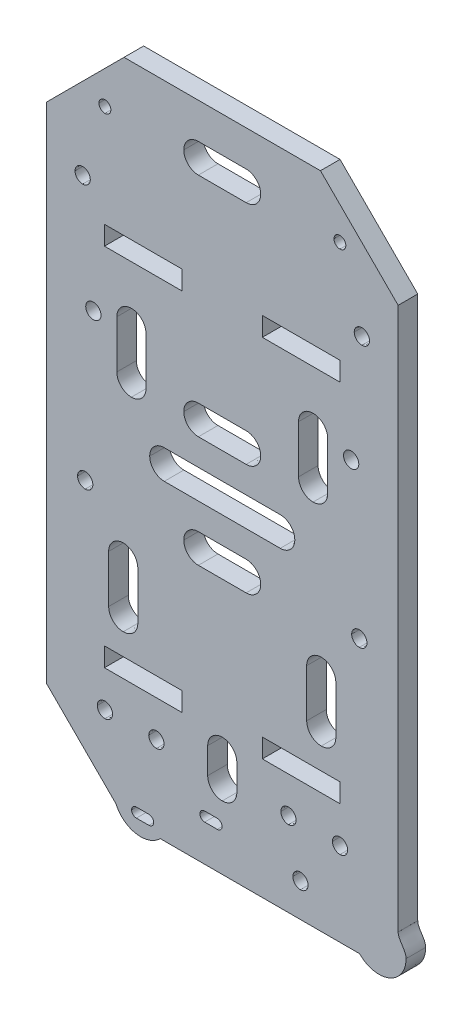
SolidWorks part; units mm, degrees
ref_plane "Front Plane" through (0, 0, 0) normal (0, 0, 1) x (1, 0, 0)
ref_plane "Top Plane" through (0, 0, 0) normal (0, 1, 0) x (1, 0, 0)
ref_plane "Right Plane" through (0, 0, 0) normal (1, 0, 0) x (0, 0, -1)
sketch "Model" plane through (0, 0, 0) normal (0, 0, 1) x (1, 0, 0)
  line L346 (206.5657, 107.1804) -> (231.766, 107.1804)
  line L347 (231.766, 107.1804) -> (231.766, 113.3307)
  line L348 (231.766, 113.3307) -> (206.5657, 113.3307)
  line L349 (206.5657, 113.3307) -> (206.5657, 107.1804)
  line L350 (257.7681, 107.1804) -> (282.967, 107.1804)
  line L351 (282.967, 107.1804) -> (282.967, 113.3307)
  line L352 (282.967, 113.3307) -> (257.7681, 113.3307)
  line L353 (257.7681, 113.3307) -> (257.7681, 107.1804)
  line L354 (212.9157, 163.4013) -> (187.7152, 138.2012)
  line L355 (187.7152, 138.2012) -> (187.7152, -24.9816)
  line L356 (187.7152, -24.9816) -> (210.2785, -47.5428)
  line L357 (224.6147, -50.1787) -> (289.3019, -50.1637)
  line L358 (301.8191, -37.8264) -> (301.8149, -37.8235)
  line L359 (301.8149, -37.8235) -> (301.8149, 138.2012)
  line L360 (301.8149, 138.2012) -> (276.6145, 163.4013)
  line L361 (276.6145, 163.4013) -> (212.9157, 163.4013)
  line L362 (206.5657, -11.2235) -> (231.766, -11.2235)
  line L363 (231.766, -11.2235) -> (231.766, -5.0731)
  line L364 (231.766, -5.0731) -> (206.5657, -5.0731)
  line L365 (206.5657, -5.0731) -> (206.5657, -11.2235)
  line L366 (257.7681, -11.2235) -> (282.967, -11.2235)
  line L367 (282.967, -11.2235) -> (282.967, -5.0731)
  line L368 (282.967, -5.0731) -> (257.7681, -5.0731)
  line L369 (257.7681, -5.0731) -> (257.7681, -11.2235)
  line L370 (220.0256, 89.3636) -> (220.0256, 73.8666)
  line L371 (210.5775, 73.8666) -> (210.5775, 89.3636)
  line L372 (278.9568, 89.3636) -> (278.9568, 73.8666)
  line L373 (269.5045, 73.8666) -> (269.5045, 89.3636)
  line L374 (239.063, -35.2158) -> (243.1413, -35.2158)
  line L375 (243.1413, -38.3181) -> (239.063, -38.3181)
  line L376 (237.0197, 42.2282) -> (252.5146, 42.2282)
  line L377 (252.5146, 32.7776) -> (237.0197, 32.7776)
  line L378 (225.9644, 60.2763) -> (263.574, 60.2763)
  line L379 (263.574, 50.827) -> (225.9644, 50.827)
  line L380 (237.0197, 78.3244) -> (252.5146, 78.3244)
  line L381 (252.5146, 68.8751) -> (237.0197, 68.8751)
  line L382 (216.9109, -45.1768) -> (220.9891, -45.1768)
  line L383 (220.9891, -48.2787) -> (216.9109, -48.2787)
  line L384 (217.3802, 22.1596) -> (217.3802, 6.6627)
  line L385 (207.9321, 6.6627) -> (207.9321, 22.1596)
  line L386 (281.6022, 22.1596) -> (281.6022, 6.6627)
  line L387 (272.15, 6.6627) -> (272.15, 22.1596)
  line L388 (249.4912, -16.3591) -> (249.4912, -24.7955)
  line L389 (240.0431, -24.7955) -> (240.0431, -16.3591)
  line L390 (237.0197, 151.8231) -> (252.5146, 151.8231)
  line L391 (252.5146, 142.3742) -> (237.0197, 142.3742)
  circle A0 centre (202.9651, 87.2011) radius 2.4743
  circle A1 centre (286.5734, 87.2011) radius 2.4743
  spline S738 degree 3 poles (210.2785, -47.5428) (211.6324, -50.6488) (214.7305, -52.8217) (218.3354, -52.8217) knots 0.2 0.2 0.2 0.2 0.266667 0.266667 0.266667 0.266667
  spline S739 degree 3 poles (218.3354, -52.8217) (220.7981, -52.8217) (223.0199, -51.8087) (224.6147, -50.1787) knots 0.266667 0.266667 0.266667 0.266667 0.333333 0.333333 0.333333 0.333333
  spline S740 degree 3 poles (289.3019, -50.1637) (290.8967, -51.8021) (293.1268, -52.8217) (295.5937, -52.8217) knots 0.4 0.4 0.4 0.4 0.466667 0.466667 0.466667 0.466667
  spline S741 degree 3 poles (295.5937, -52.8217) (298.0481, -52.8217) (300.2659, -51.8158) (301.8606, -50.1941) knots 0.466667 0.466667 0.466667 0.466667 0.533333 0.533333 0.533333 0.533333
  spline S742 degree 3 poles (301.8606, -50.1941) (303.4221, -48.608) (304.3856, -46.4318) (304.3856, -44.0314) knots 0.533333 0.533333 0.533333 0.533333 0.6 0.6 0.6 0.6
  spline S743 degree 3 poles (304.3856, -44.0314) (304.3856, -41.6085) (301.8315, -40.0711) (301.8191, -37.8264) knots 0.6 0.6 0.6 0.6 0.666667 0.666667 0.666667 0.666667
  spline S744 degree 3 poles (215.3037, 94.0893) (217.9201, 94.0893) (220.0256, 91.9808) (220.0256, 89.3636) knots 0 0 0 0 0.142857 0.142857 0.142857 0.142857
  spline S745 degree 3 poles (220.0256, 73.8666) (220.0256, 71.2498) (217.9201, 69.1426) (215.3037, 69.1426) knots 0.285714 0.285714 0.285714 0.285714 0.428571 0.428571 0.428571 0.428571
  spline S746 degree 3 poles (215.3037, 69.1426) (212.6873, 69.1426) (210.5775, 71.2498) (210.5775, 73.8666) knots 0.428571 0.428571 0.428571 0.428571 0.571429 0.571429 0.571429 0.571429
  spline S747 degree 3 poles (210.5775, 89.3636) (210.5775, 91.9808) (212.6873, 94.0893) (215.3037, 94.0893) knots 0.714286 0.714286 0.714286 0.714286 1 1 1 1
  spline S748 degree 3 poles (274.2307, 94.0893) (276.8471, 94.0893) (278.9568, 91.9808) (278.9568, 89.3636) knots 0 0 0 0 0.142857 0.142857 0.142857 0.142857
  spline S749 degree 3 poles (278.9568, 73.8666) (278.9568, 71.2498) (276.8471, 69.1426) (274.2307, 69.1426) knots 0.285714 0.285714 0.285714 0.285714 0.428571 0.428571 0.428571 0.428571
  spline S750 degree 3 poles (274.2307, 69.1426) (271.6143, 69.1426) (269.5045, 71.2498) (269.5045, 73.8666) knots 0.428571 0.428571 0.428571 0.428571 0.571429 0.571429 0.571429 0.571429
  spline S751 degree 3 poles (269.5045, 89.3636) (269.5045, 91.9808) (271.6143, 94.0893) (274.2307, 94.0893) knots 0.714286 0.714286 0.714286 0.714286 1 1 1 1
  spline S752 degree 3 poles (208.6381, 146.4724) (208.6381, 145.4088) (207.7784, 144.547) (206.7111, 144.547) knots 0 0 0 0 0.2 0.2 0.2 0.2
  spline S753 degree 3 poles (206.7111, 144.547) (205.6521, 144.547) (204.7882, 145.4088) (204.7882, 146.4724) knots 0.2 0.2 0.2 0.2 0.4 0.4 0.4 0.4
  spline S754 degree 3 poles (204.7882, 146.4724) (204.7882, 147.5347) (205.6521, 148.3973) (206.7111, 148.3973) knots 0.4 0.4 0.4 0.4 0.6 0.6 0.6 0.6
  spline S755 degree 3 poles (206.7111, 148.3973) (207.7784, 148.3973) (208.6381, 147.5347) (208.6381, 146.4724) knots 0.6 0.6 0.6 0.6 1 1 1 1
  spline S756 degree 3 poles (284.8374, 146.4724) (284.8374, 145.4088) (283.9778, 144.547) (282.9146, 144.547) knots 0 0 0 0 0.2 0.2 0.2 0.2
  spline S757 degree 3 poles (282.9146, 144.547) (281.8514, 144.547) (280.9876, 145.4088) (280.9876, 146.4724) knots 0.2 0.2 0.2 0.2 0.4 0.4 0.4 0.4
  spline S758 degree 3 poles (280.9876, 146.4724) (280.9876, 147.5347) (281.8514, 148.3973) (282.9146, 148.3973) knots 0.4 0.4 0.4 0.4 0.6 0.6 0.6 0.6
  spline S759 degree 3 poles (282.9146, 148.3973) (283.9778, 148.3973) (284.8374, 147.5347) (284.8374, 146.4724) knots 0.6 0.6 0.6 0.6 1 1 1 1
  spline S760 degree 3 poles (243.1413, -35.2158) (244.0009, -35.2158) (244.6945, -35.9077) (244.6945, -36.7678) knots 0.142857 0.142857 0.142857 0.142857 0.285714 0.285714 0.285714 0.285714
  spline S761 degree 3 poles (244.6945, -36.7678) (244.6945, -37.6262) (244.0009, -38.3181) (243.1413, -38.3181) knots 0.285714 0.285714 0.285714 0.285714 0.428571 0.428571 0.428571 0.428571
  spline S762 degree 3 poles (239.063, -38.3181) (238.2033, -38.3181) (237.5139, -37.6262) (237.5139, -36.7678) knots 0.571429 0.571429 0.571429 0.571429 0.714286 0.714286 0.714286 0.714286
  spline S763 degree 3 poles (237.5139, -36.7678) (237.5139, -35.9077) (238.2033, -35.2158) (239.063, -35.2158) knots 0.714286 0.714286 0.714286 0.714286 1 1 1 1
  spline S764 degree 3 poles (232.2936, 37.5029) (232.2936, 40.1197) (234.4033, 42.2282) (237.0197, 42.2282) knots 0 0 0 0 0.142857 0.142857 0.142857 0.142857
  spline S765 degree 3 poles (252.5146, 42.2282) (255.131, 42.2282) (257.2407, 40.1197) (257.2407, 37.5029) knots 0.285714 0.285714 0.285714 0.285714 0.428571 0.428571 0.428571 0.428571
  spline S766 degree 3 poles (257.2407, 37.5029) (257.2407, 34.8861) (255.131, 32.7776) (252.5146, 32.7776) knots 0.428571 0.428571 0.428571 0.428571 0.571429 0.571429 0.571429 0.571429
  spline S767 degree 3 poles (237.0197, 32.7776) (234.4033, 32.7776) (232.2936, 34.8861) (232.2936, 37.5029) knots 0.714286 0.714286 0.714286 0.714286 1 1 1 1
  spline S768 degree 3 poles (221.2383, 55.551) (221.2383, 58.1695) (223.3439, 60.2763) (225.9644, 60.2763) knots 0 0 0 0 0.142857 0.142857 0.142857 0.142857
  spline S769 degree 3 poles (263.574, 60.2763) (266.1904, 60.2763) (268.296, 58.1695) (268.296, 55.551) knots 0.285714 0.285714 0.285714 0.285714 0.428571 0.428571 0.428571 0.428571
  spline S770 degree 3 poles (268.296, 55.551) (268.296, 52.9342) (266.1904, 50.827) (263.574, 50.827) knots 0.428571 0.428571 0.428571 0.428571 0.571429 0.571429 0.571429 0.571429
  spline S771 degree 3 poles (225.9644, 50.827) (223.3439, 50.827) (221.2383, 52.9342) (221.2383, 55.551) knots 0.714286 0.714286 0.714286 0.714286 1 1 1 1
  spline S772 degree 3 poles (232.2936, 73.5992) (232.2936, 76.2172) (234.4033, 78.3244) (237.0197, 78.3244) knots 0 0 0 0 0.142857 0.142857 0.142857 0.142857
  spline S773 degree 3 poles (252.5146, 78.3244) (255.131, 78.3244) (257.2407, 76.2172) (257.2407, 73.5992) knots 0.285714 0.285714 0.285714 0.285714 0.428571 0.428571 0.428571 0.428571
  spline S774 degree 3 poles (257.2407, 73.5992) (257.2407, 70.9823) (255.131, 68.8751) (252.5146, 68.8751) knots 0.428571 0.428571 0.428571 0.428571 0.571429 0.571429 0.571429 0.571429
  spline S775 degree 3 poles (237.0197, 68.8751) (234.4033, 68.8751) (232.2936, 70.9823) (232.2936, 73.5992) knots 0.714286 0.714286 0.714286 0.714286 1 1 1 1
  spline S776 degree 3 poles (220.9891, -45.1768) (221.8488, -45.1768) (222.5423, -45.8683) (222.5423, -46.7267) knots 0.142857 0.142857 0.142857 0.142857 0.285714 0.285714 0.285714 0.285714
  spline S777 degree 3 poles (222.5423, -46.7267) (222.5423, -47.5868) (221.8488, -48.2787) (220.9891, -48.2787) knots 0.285714 0.285714 0.285714 0.285714 0.428571 0.428571 0.428571 0.428571
  spline S778 degree 3 poles (216.9109, -48.2787) (216.0512, -48.2787) (215.3618, -47.5868) (215.3618, -46.7267) knots 0.571429 0.571429 0.571429 0.571429 0.714286 0.714286 0.714286 0.714286
  spline S779 degree 3 poles (215.3618, -46.7267) (215.3618, -45.8683) (216.0512, -45.1768) (216.9109, -45.1768) knots 0.714286 0.714286 0.714286 0.714286 1 1 1 1
  spline S780 degree 3 poles (212.6582, 26.8849) (215.2746, 26.8849) (217.3802, 24.7764) (217.3802, 22.1596) knots 0 0 0 0 0.142857 0.142857 0.142857 0.142857
  spline S781 degree 3 poles (217.3802, 6.6627) (217.3802, 4.0454) (215.2746, 1.9386) (212.6582, 1.9386) knots 0.285714 0.285714 0.285714 0.285714 0.428571 0.428571 0.428571 0.428571
  spline S782 degree 3 poles (212.6582, 1.9386) (210.0418, 1.9386) (207.9321, 4.0454) (207.9321, 6.6627) knots 0.428571 0.428571 0.428571 0.428571 0.571429 0.571429 0.571429 0.571429
  spline S783 degree 3 poles (207.9321, 22.1596) (207.9321, 24.7764) (210.0418, 26.8849) (212.6582, 26.8849) knots 0.714286 0.714286 0.714286 0.714286 1 1 1 1
  spline S784 degree 3 poles (276.8761, 26.8849) (279.4925, 26.8849) (281.6022, 24.7764) (281.6022, 22.1596) knots 0 0 0 0 0.142857 0.142857 0.142857 0.142857
  spline S785 degree 3 poles (281.6022, 6.6627) (281.6022, 4.0454) (279.4925, 1.9386) (276.8761, 1.9386) knots 0.285714 0.285714 0.285714 0.285714 0.428571 0.428571 0.428571 0.428571
  spline S786 degree 3 poles (276.8761, 1.9386) (274.2597, 1.9386) (272.15, 4.0454) (272.15, 6.6627) knots 0.428571 0.428571 0.428571 0.428571 0.571429 0.571429 0.571429 0.571429
  spline S787 degree 3 poles (272.15, 22.1596) (272.15, 24.7764) (274.2597, 26.8849) (276.8761, 26.8849) knots 0.714286 0.714286 0.714286 0.714286 1 1 1 1
  spline S788 degree 3 poles (201.9642, 123.5586) (201.9642, 124.9253) (200.8595, 126.0321) (199.4932, 126.0321) knots 0 0 0 0 0.2 0.2 0.2 0.2
  spline S789 degree 3 poles (199.4932, 126.0321) (198.1268, 126.0321) (197.018, 124.9253) (197.018, 123.5586) knots 0.2 0.2 0.2 0.2 0.4 0.4 0.4 0.4
  spline S790 degree 3 poles (197.018, 123.5586) (197.018, 122.1926) (198.1268, 121.0846) (199.4932, 121.0846) knots 0.4 0.4 0.4 0.4 0.6 0.6 0.6 0.6
  spline S791 degree 3 poles (199.4932, 121.0846) (200.8595, 121.0846) (201.9642, 122.1926) (201.9642, 123.5586) knots 0.6 0.6 0.6 0.6 1 1 1 1
  spline S792 degree 3 poles (292.5163, 123.5586) (292.5163, 124.9253) (291.4075, 126.0321) (290.0412, 126.0321) knots 0 0 0 0 0.2 0.2 0.2 0.2
  spline S793 degree 3 poles (290.0412, 126.0321) (288.6748, 126.0321) (287.5701, 124.9253) (287.5701, 123.5586) knots 0.2 0.2 0.2 0.2 0.4 0.4 0.4 0.4
  spline S794 degree 3 poles (287.5701, 123.5586) (287.566, 122.1926) (288.6748, 121.0846) (290.0412, 121.0846) knots 0.4 0.4 0.4 0.4 0.6 0.6 0.6 0.6
  spline S795 degree 3 poles (290.0412, 121.0846) (291.4075, 121.0846) (292.5163, 122.1926) (292.5163, 123.5586) knots 0.6 0.6 0.6 0.6 1 1 1 1
  spline S804 degree 3 poles (202.7907, 38.3019) (202.7907, 39.6691) (201.6818, 40.7771) (200.3155, 40.7771) knots 0 0 0 0 0.2 0.2 0.2 0.2
  spline S805 degree 3 poles (200.3155, 40.7771) (198.9491, 40.7771) (197.8444, 39.6691) (197.8444, 38.3019) knots 0.2 0.2 0.2 0.2 0.4 0.4 0.4 0.4
  spline S806 degree 3 poles (197.8444, 38.3019) (197.8444, 36.9364) (198.9491, 35.8284) (200.3155, 35.8284) knots 0.4 0.4 0.4 0.4 0.6 0.6 0.6 0.6
  spline S807 degree 3 poles (200.3155, 35.8284) (201.6818, 35.8284) (202.7907, 36.9364) (202.7907, 38.3019) knots 0.6 0.6 0.6 0.6 1 1 1 1
  spline S808 degree 3 poles (291.6899, 38.3019) (291.6899, 39.6691) (290.581, 40.7771) (289.2189, 40.7771) knots 0 0 0 0 0.2 0.2 0.2 0.2
  spline S809 degree 3 poles (289.2189, 40.7771) (287.8484, 40.7771) (286.7437, 39.6691) (286.7437, 38.3019) knots 0.2 0.2 0.2 0.2 0.4 0.4 0.4 0.4
  spline S810 degree 3 poles (286.7437, 38.3019) (286.7437, 36.9364) (287.8484, 35.8284) (289.2189, 35.8284) knots 0.4 0.4 0.4 0.4 0.6 0.6 0.6 0.6
  spline S811 degree 3 poles (289.2189, 35.8284) (290.581, 35.8284) (291.6899, 36.9364) (291.6899, 38.3019) knots 0.6 0.6 0.6 0.6 1 1 1 1
  spline S812 degree 3 poles (209.1863, -22.9719) (209.1863, -21.6052) (208.0816, -20.4984) (206.7111, -20.4984) knots 0 0 0 0 0.2 0.2 0.2 0.2
  spline S813 degree 3 poles (206.7111, -20.4984) (205.3489, -20.4984) (204.2401, -21.6052) (204.2401, -22.9719) knots 0.2 0.2 0.2 0.2 0.4 0.4 0.4 0.4
  spline S814 degree 3 poles (204.2401, -22.9719) (204.2401, -24.3379) (205.3489, -25.4459) (206.7111, -25.4459) knots 0.4 0.4 0.4 0.4 0.6 0.6 0.6 0.6
  spline S815 degree 3 poles (206.7111, -25.4459) (208.0816, -25.4459) (209.1863, -24.3379) (209.1863, -22.9719) knots 0.6 0.6 0.6 0.6 1 1 1 1
  spline S816 degree 3 poles (225.8772, -22.9719) (225.8772, -21.6052) (224.7684, -20.4984) (223.402, -20.4984) knots 0 0 0 0 0.2 0.2 0.2 0.2
  spline S817 degree 3 poles (223.402, -20.4984) (222.0357, -20.4984) (220.9268, -21.6052) (220.9268, -22.9719) knots 0.2 0.2 0.2 0.2 0.4 0.4 0.4 0.4
  spline S818 degree 3 poles (220.9268, -22.9719) (220.9268, -24.3379) (222.0357, -25.4459) (223.402, -25.4459) knots 0.4 0.4 0.4 0.4 0.6 0.6 0.6 0.6
  spline S819 degree 3 poles (223.402, -25.4459) (224.7684, -25.4459) (225.8772, -24.3379) (225.8772, -22.9719) knots 0.6 0.6 0.6 0.6 1 1 1 1
  spline S820 degree 3 poles (268.7238, -22.9719) (268.7238, -21.6052) (267.6149, -20.4984) (266.2486, -20.4984) knots 0 0 0 0 0.2 0.2 0.2 0.2
  spline S821 degree 3 poles (266.2486, -20.4984) (264.8822, -20.4984) (263.7775, -21.6052) (263.7775, -22.9719) knots 0.2 0.2 0.2 0.2 0.4 0.4 0.4 0.4
  spline S822 degree 3 poles (263.7775, -22.9719) (263.7775, -24.3379) (264.8822, -25.4459) (266.2486, -25.4459) knots 0.4 0.4 0.4 0.4 0.6 0.6 0.6 0.6
  spline S823 degree 3 poles (266.2486, -25.4459) (267.6149, -25.4459) (268.7238, -24.3379) (268.7238, -22.9719) knots 0.6 0.6 0.6 0.6 1 1 1 1
  spline S824 degree 3 poles (285.4313, -23.0164) (285.4313, -21.6492) (284.3225, -20.5424) (282.9561, -20.5424) knots 0 0 0 0 0.2 0.2 0.2 0.2
  spline S825 degree 3 poles (282.9561, -20.5424) (281.5898, -20.5424) (280.4851, -21.6492) (280.4851, -23.0164) knots 0.2 0.2 0.2 0.2 0.4 0.4 0.4 0.4
  spline S826 degree 3 poles (280.4851, -23.0164) (280.4851, -24.3819) (281.5898, -25.4899) (282.9561, -25.4899) knots 0.4 0.4 0.4 0.4 0.6 0.6 0.6 0.6
  spline S827 degree 3 poles (282.9561, -25.4899) (284.3225, -25.4899) (285.4313, -24.3819) (285.4313, -23.0164) knots 0.6 0.6 0.6 0.6 1 1 1 1
  spline S828 degree 3 poles (272.6068, -39.3132) (272.6068, -37.9473) (271.498, -36.8392) (270.1316, -36.8392) knots 0 0 0 0 0.2 0.2 0.2 0.2
  spline S829 degree 3 poles (270.1316, -36.8392) (268.7653, -36.8392) (267.6606, -37.9473) (267.6606, -39.3132) knots 0.2 0.2 0.2 0.2 0.4 0.4 0.4 0.4
  spline S830 degree 3 poles (267.6606, -39.3132) (267.6606, -40.6787) (268.7653, -41.7867) (270.1316, -41.7867) knots 0.4 0.4 0.4 0.4 0.6 0.6 0.6 0.6
  spline S831 degree 3 poles (270.1316, -41.7867) (271.498, -41.7867) (272.6068, -40.6799) (272.6068, -39.3132) knots 0.6 0.6 0.6 0.6 1 1 1 1
  spline S832 degree 3 poles (244.7692, -11.6338) (247.3856, -11.6338) (249.4912, -13.7406) (249.4912, -16.3591) knots 0 0 0 0 0.142857 0.142857 0.142857 0.142857
  spline S833 degree 3 poles (249.4912, -24.7955) (249.4912, -27.4123) (247.3856, -29.5208) (244.7692, -29.5208) knots 0.285714 0.285714 0.285714 0.285714 0.428571 0.428571 0.428571 0.428571
  spline S834 degree 3 poles (244.7692, -29.5208) (242.1487, -29.5208) (240.0431, -27.4123) (240.0431, -24.7955) knots 0.428571 0.428571 0.428571 0.428571 0.571429 0.571429 0.571429 0.571429
  spline S835 degree 3 poles (240.0431, -16.3591) (240.0431, -13.7406) (242.1487, -11.6338) (244.7692, -11.6338) knots 0.714286 0.714286 0.714286 0.714286 1 1 1 1
  spline S836 degree 3 poles (232.2936, 147.0982) (232.2936, 149.7163) (234.4033, 151.8231) (237.0197, 151.8231) knots 0 0 0 0 0.142857 0.142857 0.142857 0.142857
  spline S837 degree 3 poles (252.5146, 151.8231) (255.131, 151.8231) (257.2407, 149.7163) (257.2407, 147.0982) knots 0.285714 0.285714 0.285714 0.285714 0.428571 0.428571 0.428571 0.428571
  spline S838 degree 3 poles (257.2407, 147.0982) (257.2407, 144.481) (255.131, 142.3742) (252.5146, 142.3742) knots 0.428571 0.428571 0.428571 0.428571 0.571429 0.571429 0.571429 0.571429
  spline S839 degree 3 poles (237.0197, 142.3742) (234.4033, 142.3742) (232.2936, 144.481) (232.2936, 147.0982) knots 0.714286 0.714286 0.714286 0.714286 1 1 1 1
extrude "Boss-Extrude1" add sketch "Model" along normal blind 6.35
